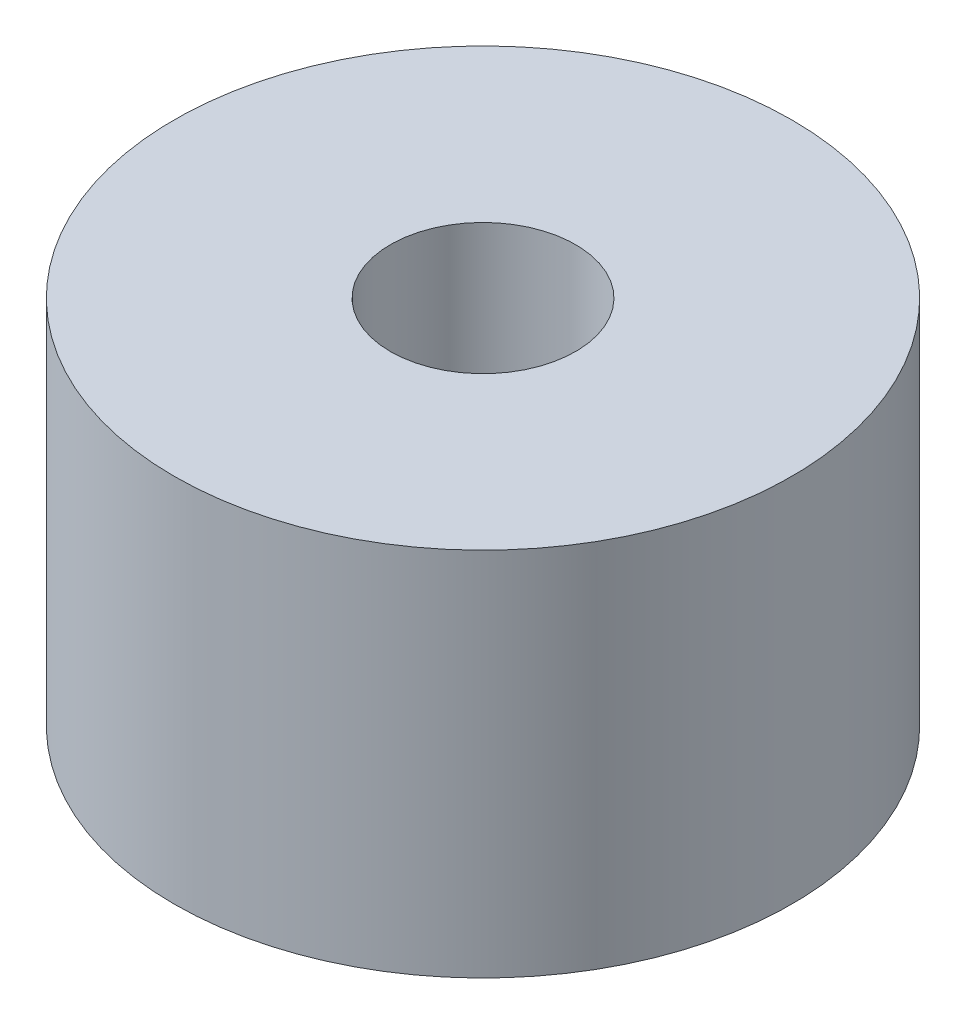
SolidWorks part; units mm, degrees
ref_plane "前视基准面" through (0, 0, 0) normal (0, 0, 1) x (1, 0, 0)
ref_plane "上视基准面" through (0, 0, 0) normal (0, 1, 0) x (1, 0, 0)
ref_plane "右视基准面" through (0, 0, 0) normal (1, 0, 0) x (0, 0, -1)
other "Configuration Table"
sketch "草图1" plane through (0, 0, 0) normal (0, 1, 0) x (1, 0, 0)
  circle A0 centre (0, 0) radius 5
  dimension "D1" = 10
extrude "凸台-拉伸1" add sketch "草图1" along normal blind 3
sketch "草图2" plane through (0, 3, 0) normal (0, 1, 0) x (1, 0, 0)
  circle A0 centre (0, 0) radius 1.5
  circle A1 centre (0, 0) radius 5
  circle A2 centre (0, 0) radius 5
  dimension "D2" = 3
  dimension "D1" = 0
extrude "凸台-拉伸2" add sketch "草图2" along normal blind 3
